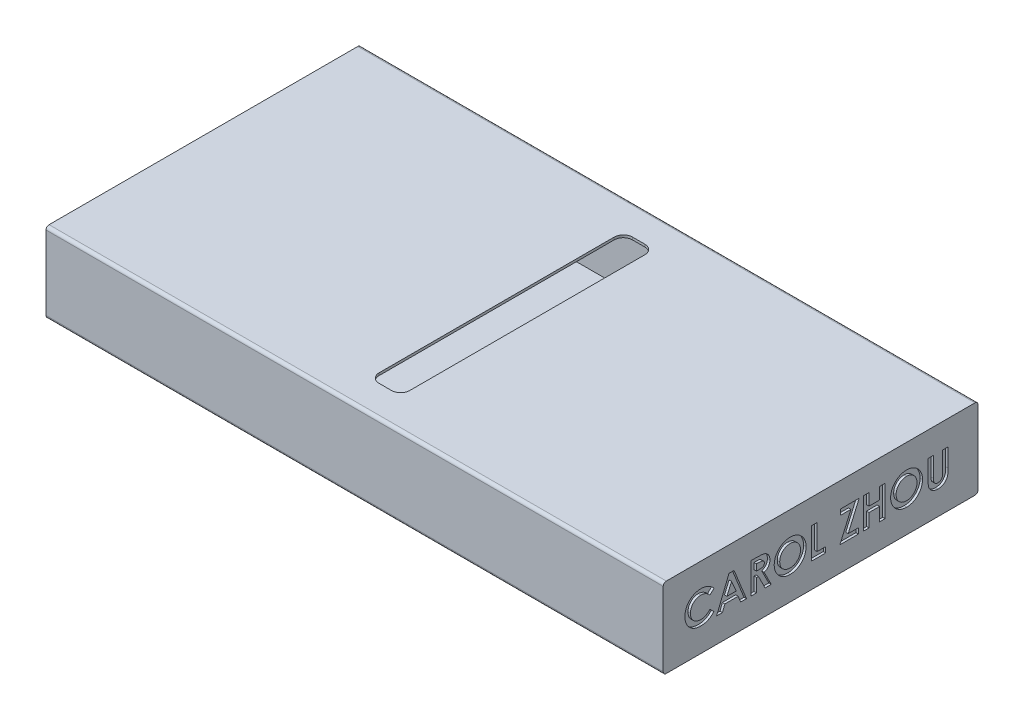
SolidWorks part; units mm, degrees
ref_plane "Front Plane" through (0, 0, 0) normal (0, 0, 1) x (1, 0, 0)
ref_plane "Top Plane" through (0, 0, 0) normal (0, 1, 0) x (1, 0, 0)
ref_plane "Right Plane" through (0, 0, 0) normal (1, 0, 0) x (0, 0, -1)
sketch "Sketch1" plane through (0, 0, 0) normal (1, 0, 0) x (0, 0, -1)
  line L1 (51.3, -13.05) -> (-51.3, -13.05)
  line L2 (51.3, -13.05) -> (51.3, 13.05)
  line L3 (51.3, 13.05) -> (-51.3, 13.05)
  line L4 (-51.3, -13.05) -> (-51.3, 13.05)
  line L5 (0, 13.05) -> (0, -13.05) construction
  line L6 (51.3, 0) -> (-51.3, 0) construction
  point P0 (0, 0)
  dimension "D1" = 26.1
  dimension "D2" = 102.6
extrude "Boss-Extrude1" add sketch "Sketch1" along normal blind 1.2
sketch "Sketch2" plane through (0, 0, 0) normal (-1, 0, 0) x (0, 0, 1)
  line L0 (-50.5, -12.25) -> (50.5, -12.25)
  line L1 (50.5, -12.25) -> (50.5, 12.25)
  line L2 (50.5, 12.25) -> (-50.5, 12.25)
  line L3 (-50.5, 12.25) -> (-50.5, -12.25)
  line L4 (51.3, -13.05) -> (51.3, 13.05)
  line L5 (51.3, 13.05) -> (-51.3, 13.05)
  line L6 (-51.3, 13.05) -> (-51.3, -13.05)
  line L7 (-51.3, -13.05) -> (51.3, -13.05)
  line L8 (51.3, -13.05) -> (51.3, 13.05)
  line L9 (51.3, 13.05) -> (-51.3, 13.05)
  line L10 (-51.3, 13.05) -> (-51.3, -13.05)
  line L11 (-51.3, -13.05) -> (51.3, -13.05)
  dimension "D1" = 0
  dimension "D2" = 0.8
extrude "Boss-Extrude2" add sketch "Sketch2" along normal blind 200
sketch "Sketch3" plane through (1.2, 0, 0) normal (1, 0, 0) x (0, 0, -1)
  line L0 (-51.3, -5) -> (51.3, -5) construction
  line L1 (-51.3, 13.05) -> (-51.3, -13.05) construction
  line L2 (51.3, -13.05) -> (51.3, 13.05) construction
  text T0 "<b>CAROL ZHOU</b>" font "Century Gothic" height 10
  dimension "D1" = 5
extrude "Cut-Extrude1" cut sketch "Sketch3" against normal blind 0.8
sketch "Sketch4" plane through (0, 13.05, 0) normal (0, 1, 0) x (1, 0, 0)
  line L0 (-200, 51.3) -> (1.2, -51.3) construction
  line L1 (1.2, 51.3) -> (-200, -51.3) construction
  line L3 (-104.4, 41.3) -> (-94.4, 41.3)
  line L4 (1.2, 51.3) -> (-200, 51.3)
  line L5 (-200, 51.3) -> (-200, -51.3)
  line L6 (-200, -51.3) -> (1.2, -51.3)
  line L7 (1.2, -51.3) -> (1.2, 51.3)
  line L8 (1.2, 51.3) -> (-200, 51.3)
  line L9 (-200, 51.3) -> (-200, -51.3)
  line L10 (-200, -51.3) -> (1.2, -51.3)
  line L11 (1.2, -51.3) -> (1.2, 51.3)
  line L12 (-104.4, 41.3) -> (-104.4, -41.3)
  line L13 (-104.4, -41.3) -> (-94.4, -41.3)
  line L14 (-94.4, 41.3) -> (-94.4, -41.3)
  line L15 (-99.4, -41.3) -> (-99.4, 41.3) construction
  line L16 (-104.4, 0) -> (-94.4, 0) construction
  point P2 (-99.4, 0)
  dimension "D2" = 10
  dimension "D3" = 10
  dimension "D1" = 0
extrude "Cut-Extrude3" cut sketch "Sketch4" against normal up to surface (0.8 mm away) contours L14 L3 L12 L13 up to face at (-100, 12.25, 0)
fillet "Fillet1" radius 3 4 edges at (-104.4, 12.65, 41.3) (-104.4, 12.65, -41.3) (-94.4, 12.65, 41.3) (-94.4, 12.65, -41.3)
fillet "Fillet2" radius 1 4 edges at (-99.4, 13.05, 51.3) (-99.4, -13.05, -51.3) (-99.4, -13.05, 51.3) (-99.4, 13.05, -51.3)
equation "\"D2@Sketch1\"=101+1.6"
equation "\"D1@Sketch1\"=24.5+1.6"
